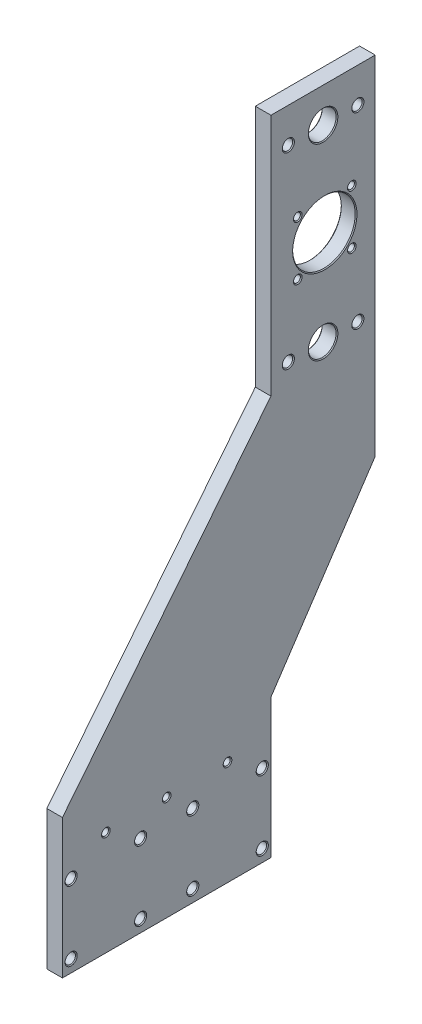
SolidWorks part; units mm, degrees
ref_plane "Alzado" through (0, 0, 0) normal (0, 0, 1) x (1, 0, 0)
ref_plane "Planta" through (0, 0, 0) normal (0, 1, 0) x (1, 0, 0)
ref_plane "Vista lateral" through (0, 0, 0) normal (1, 0, 0) x (0, 0, -1)
sketch "Croquis1" plane through (0, 0, 0) normal (1, 0, 0) x (0, 0, -1)
  line L0 (-294.7966, -440.4595) -> (-174.7966, -290.4595)
  line L1 (-174.7966, -150.4595) -> (-114.7966, -150.4595)
  line L2 (-174.7966, -150.4595) -> (-174.7966, -290.4595)
  line L3 (-294.7966, -440.4595) -> (-294.7966, -520.4595)
  line L4 (-114.7966, -150.4595) -> (-114.7966, -350.4595)
  line L5 (-174.7966, -440.4595) -> (-174.7966, -520.4595)
  line L6 (-294.7966, -520.4595) -> (-174.7966, -520.4595)
  line L7 (-114.7966, -350.4595) -> (-174.7966, -440.4595)
  point P0 (-82.2625, -137.8814)
  dimension "D1" = 60
  dimension "D2" = 200
  dimension "D3" = 80
  dimension "D4" = 120
  dimension "D5" = 80
  dimension "D6" = 60
  dimension "D7" = 370
  dimension "D8" = 140
extrude "Saliente-Extruir1" add sketch "Croquis1" along normal mid plane 9
sketch "Croquis4" plane through (4.5, 0, 0) normal (1, 0, 0) x (0, 0, -1)
  line L0 (-174.7966, -350.4595) -> (-114.7966, -350.4595) construction
  line L1 (-174.7966, -150.4595) -> (-174.7966, -350.4595) construction
  line L2 (-143.7966, -156.15) -> (-143.7966, -256.5842) construction
  line L3 (-114.7966, -150.4595) -> (-174.7966, -150.4595) construction
  line L4 (-159.353, -208.9031) -> (-159.353, -240.0158) construction
  circle A0 centre (-143.7966, -224.4595) radius 18
  circle A1 centre (-159.353, -208.9031) radius 2
  circle A2 centre (-128.2403, -208.9031) radius 2
  circle A3 centre (-128.2403, -240.0158) radius 2
  circle A4 centre (-159.353, -240.0158) radius 2
  point P25 (-143.7966, -224.4595)
  dimension "D1" = 74
  dimension "D2" = 36
  dimension "D3" = 4
  dimension "D4" = 4
  dimension "D5" = 22
  dimension "D6" = 22
  dimension "D7" = 22
  dimension "D8" = 22
  dimension "D9" = 22
  dimension "D10" = 31
extrude "Cortar-Extruir3" cut sketch "Croquis4" against normal through all
chamfer "Chaflán1" distance 0.5 angle 45 5 edges at (4.5, -240.0158, 126.2403) (4.5, -240.0158, 157.353) (4.5, -208.9031, 126.2403) (4.5, -208.9031, 157.353) (4.5, -224.4595, 125.7966)
sketch "Croquis5" plane through (4.5, 0, 0) normal (1, 0, 0) x (0, 0, -1)
  line L0 (-174.7966, -350.4595) -> (-174.7966, -150.4595) construction
  line L1 (-114.7966, -350.4595) -> (-174.7966, -350.4595) construction
  line L2 (-144.7966, -150.4595) -> (-144.7966, -350.4595) construction
  line L3 (-114.7966, -150.4595) -> (-174.7966, -150.4595) construction
  line L4 (-114.7966, -170.4595) -> (-174.7966, -170.4595) construction
  line L5 (-114.7966, -350.4595) -> (-114.7966, -150.4595) construction
  line L6 (-134.7966, -278.4595) -> (-194.7966, -278.4595) construction
  line L7 (-164.7966, -170.4595) -> (-164.7966, -278.4595) construction
  line L8 (-124.7966, -170.4595) -> (-124.7966, -278.4595) construction
  circle A0 centre (-144.7966, -170.4595) radius 8
  circle A1 centre (-144.7966, -278.4595) radius 8
  circle A2 centre (-124.7966, -170.4595) radius 3
  circle A3 centre (-164.7966, -170.4595) radius 3
  circle A4 centre (-164.7966, -278.4595) radius 3
  circle A5 centre (-124.7966, -278.4595) radius 3
  dimension "D1" = 16
  dimension "D2" = 16
  dimension "D3" = 20
  dimension "D4" = 108
  dimension "D5" = 6
  dimension "D6" = 20
  dimension "D7" = 20
extrude "Cortar-Extruir4" cut sketch "Croquis5" against normal through all
chamfer "Chaflán2" distance 0.5 angle 45 6 edges at (4.5, -278.4595, 121.7966) (4.5, -278.4595, 136.7966) (4.5, -278.4595, 161.7966) (4.5, -170.4595, 121.7966) (4.5, -170.4595, 136.7966) (4.5, -170.4595, 161.7966)
sketch "Croquis3" plane through (4.5, 0, 0) normal (1, 0, 0) x (0, 0, -1)
  line L0 (-294.7966, -466.4595) -> (-174.7966, -466.4595) construction
  line L1 (-294.7966, -440.4595) -> (-294.7966, -520.4595) construction
  line L2 (-174.7966, -520.4595) -> (-174.7966, -440.4595) construction
  line L3 (-294.7966, -520.4595) -> (-174.7966, -520.4595) construction
  line L4 (-234.7966, -466.4595) -> (-234.7966, -520.4595) construction
  line L5 (-289.7966, -473.4595) -> (-289.7966, -513.4595) construction
  line L6 (-289.7966, -513.4595) -> (-249.7966, -513.4595) construction
  line L7 (-249.7966, -513.4595) -> (-249.7966, -473.4595) construction
  line L8 (-249.7966, -473.4595) -> (-289.7966, -473.4595) construction
  circle A0 centre (-289.7966, -473.4595) radius 3
  circle A1 centre (-289.7966, -513.4595) radius 3
  circle A2 centre (-249.7966, -473.4595) radius 3
  circle A3 centre (-249.7966, -513.4595) radius 3
  circle A4 centre (-219.7966, -513.4595) radius 3
  circle A5 centre (-219.7966, -473.4595) radius 3
  circle A6 centre (-179.7966, -513.4595) radius 3
  circle A7 centre (-179.7966, -473.4595) radius 3
  dimension "D6" = 6
  dimension "D7" = 54
  dimension "D1" = 40
  dimension "D2" = 40
  dimension "D3" = 5
  dimension "D4" = 7
  dimension "D5" = 7
extrude "Cortar-Extruir2" cut sketch "Croquis3" against normal through all
chamfer "Chaflán3" distance 0.5 angle 45 8 edges at (4.5, -513.4595, 182.7966) (4.5, -473.4595, 182.7966) (4.5, -513.4595, 222.7966) (4.5, -473.4595, 222.7966) (4.5, -513.4595, 246.7966) (4.5, -473.4595, 246.7966) (4.5, -513.4595, 286.7966) (4.5, -473.4595, 286.7966)
sketch "Croquis2" plane through (4.5, 0, 0) normal (1, 0, 0) x (0, 0, -1)
  line L0 (-294.7966, -460.4595) -> (-174.7966, -460.4595) construction
  line L1 (-294.7966, -440.4595) -> (-294.7966, -520.4595) construction
  line L2 (-174.7966, -520.4595) -> (-174.7966, -440.4595) construction
  line L3 (-294.7966, -520.4595) -> (-174.7966, -520.4595) construction
  circle A0 centre (-234.7966, -460.4595) radius 2
  circle A1 centre (-269.7966, -460.4595) radius 2
  circle A2 centre (-199.7966, -460.4595) radius 2
  dimension "D2" = 4
  dimension "D3" = 35
  dimension "D4" = 35
  dimension "D1" = 60
extrude "Cortar-Extruir1" cut sketch "Croquis2" against normal through all
chamfer "Chaflán4" distance 0.5 angle 45 3 edges at (4.5, -460.4595, 197.7966) (4.5, -460.4595, 232.7966) (4.5, -460.4595, 267.7966)
chamfer "Chaflán5" distance 0.5 angle 45 3 edges at (-4.5, -278.4595, 136.7966) (-4.5, -224.4595, 125.7966) (-4.5, -170.4595, 136.7966)
